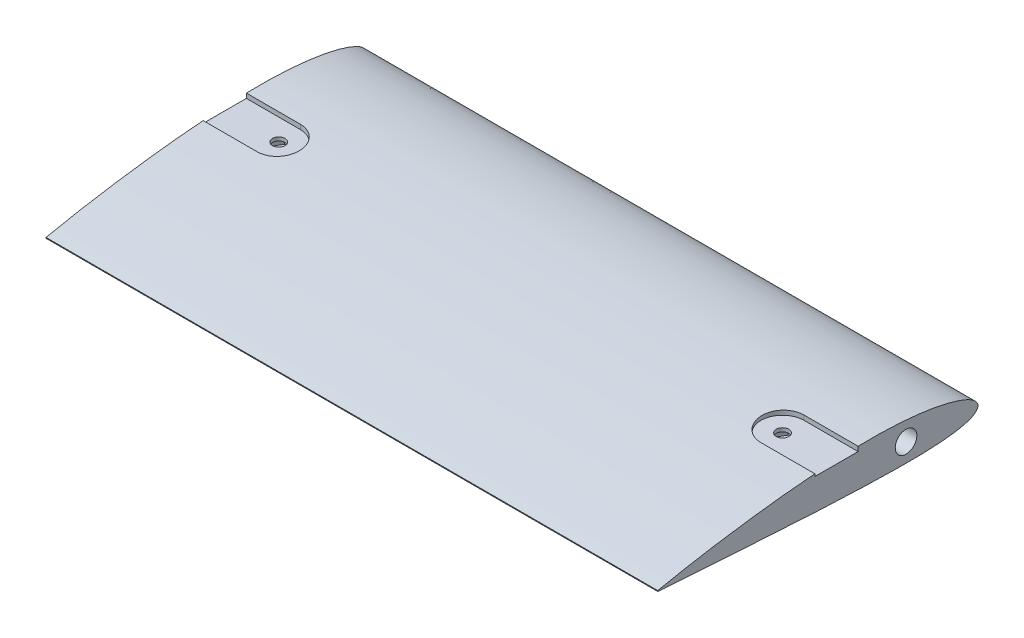
SolidWorks part; units mm, degrees
ref_plane "Front Plane" through (0, 0, 0) normal (0, 0, 1) x (1, 0, 0)
ref_plane "Top Plane" through (0, 0, 0) normal (0, 1, 0) x (1, 0, 0)
ref_plane "Right Plane" through (0, 0, 0) normal (1, 0, 0) x (0, 0, -1)
sketch "Sketch4" plane through (0, 0, 0) normal (0, 0, 1) x (1, 0, 0)
  line L0 (-30.3109, 17.5) -> (30.3109, 17.5)
  arc A1 (30.3109, 17.5) -> (-30.3109, 17.5) centre (0, 0) ccw
  dimension "D1" = 35
  dimension "D2" = 17.5
extrude "Exterior" add sketch "Sketch4" along normal blind 89 contours L0 A1
sketch "Sketch5" plane through (0, 0, 0) normal (0, 0, -1) x (-1, 0, 0)
  line L0 (30.3109, 17.5) -> (-30.3109, 17.5) construction
  line L1 (23.1247, 17.5) -> (-23.1247, 17.5)
  arc A0 (23.1247, 17.5) -> (-23.1247, 17.5) centre (0, 0) ccw
  dimension "D1" = 58
extrude "Boss-Extrude1" add sketch "Sketch5" along normal blind 15
curve "Curve3"
  spline degree 3 poles (0, 1.3, 1000) (0, 4.7133, 983.3426) (0, 11.531, 950.0715) (0, 24.0186, 883.4722) (0, 37.8548, 800.1781) (0, 52.175, 700.1592) (0, 64.1175, 600.1567) (0, 72.8619, 500.1109) (0, 78.7837, 400.0878) (0, 79.786, 316.6355) (0, 77.0249, 249.9395) (0, 72.979, 199.8766) (0, 66.5721, 149.7505) (0, 58.6825, 108.0331) (0, 49.7566, 74.7751) (0, 41.6416, 49.5609) (0, 32.1864, 28.1982) (0, 20.723, 9.771) (0, 0.8988, -6.2982) (0, -16.5264, 10.3934) (0, -24.4739, 28.476) (0, -30.5108, 49.7447) (0, -34.8393, 74.8759) (0, -38.5332, 108.2669) (0, -41.3764, 149.947) (0, -42.5163, 199.9941) (0, -42.3574, 250.0055) (0, -40.8857, 316.6783) (0, -38.2375, 400.0272) (0, -33.6287, 500.0334) (0, -27.6385, 600.0106) (0, -21.4122, 700.0048) (0, -15.1098, 800.0161) (0, -9.3053, 883.3314) (0, -4.8282, 950.0042) (0, -2.4761, 983.334) (0, -1.3, 1000) knots 0 0 0 0 0.025012 0.049959 0.099673 0.149206 0.198581 0.247805 0.296917 0.345953 0.370492 0.395091 0.419815 0.444799 0.45749 0.470406 0.483879 0.491264 0.503459 0.513609 0.520451 0.533235 0.545691 0.558032 0.582609 0.607135 0.631652 0.656174 0.705234 0.75432 0.803437 0.852566 0.901701 0.950849 0.975423 1 1 1 1
sketch "Sketch7" plane through (0, 0, 0) normal (1, 0, 0) x (0, 0, -1)
  line L0 (-89, 21.3887) -> (-89, 21.1573)
  line L1 (-89, 21.273) -> (0, 21.3903) construction
  line L2 (0, 21.3903) -> (-0.0573, 64.8516) construction
  line L7 (-89, 17.5) -> (0, 17.5) construction
  line L9 (0, 17.5) -> (0, 29) construction
  spline S1 degree 3 poles (-89, 21.3887) (-87.5176, 21.6924) (-84.5567, 22.2992) (-78.6297, 23.4105) (-71.2171, 24.6418) (-62.316, 25.9162) (-53.4164, 26.979) (-44.5129, 27.7573) (-35.6114, 28.2842) (-28.1847, 28.3735) (-22.2492, 28.1277) (-17.7939, 27.7677) (-13.3329, 27.1975) (-9.6203, 26.4954) (-6.6606, 25.701) (-4.4167, 24.9788) (-2.5155, 24.1374) (-0.8756, 23.1172) (0.5545, 21.353) (-0.931, 19.8022) (-2.5402, 19.095) (-4.433, 18.5577) (-6.6696, 18.1725) (-9.6412, 17.8438) (-13.3504, 17.5907) (-17.8043, 17.4893) (-22.255, 17.5034) (-28.1885, 17.6344) (-35.606, 17.8701) (-44.506, 18.2802) (-53.4034, 18.8133) (-62.3022, 19.3674) (-71.2026, 19.9283) (-78.6172, 20.4449) (-84.5507, 20.8433) (-87.5168, 21.0526) (-89, 21.1573) knots 0 0 0 0 0.025012 0.049959 0.099673 0.149206 0.198581 0.247805 0.296917 0.345953 0.370492 0.395091 0.419815 0.444799 0.45749 0.470406 0.483879 0.491264 0.503459 0.513609 0.520451 0.533235 0.545691 0.558032 0.582609 0.607135 0.631652 0.656174 0.705234 0.75432 0.803437 0.852566 0.901701 0.950849 0.975423 1 1 1 1
  dimension "D1" = 89
ref_plane "Plane1" through (80, 0, 0) normal (1, 0, 0) x (0, 0, -1)
ref_plane "Plane2" through (-80, 0, 0) normal (1, 0, 0) x (0, 0, -1)
sketch "Sketch8" plane through (80, 0, 0) normal (1, 0, 0) x (0, 0, -1)
  line L0 (-89, 21.3887) -> (-89, 21.1573)
  spline S0 degree 3 poles (-469.3669, 946.2185) (-209.3584, -26.81) (-147.9272, 10.417) (-78.6297, 23.4105) (-71.2171, 24.6418) (-62.316, 25.9162) (-53.4164, 26.979) (-44.5129, 27.7573) (-35.6114, 28.2842) (-28.1847, 28.3735) (-22.2492, 28.1277) (-17.7939, 27.7677) (-13.3329, 27.1975) (-9.6203, 26.4954) (-6.6606, 25.701) (-4.4167, 24.9788) (-2.5155, 24.1374) (-0.8756, 23.1172) (0.5545, 21.353) (-0.931, 19.8022) (-2.5402, 19.095) (-4.433, 18.5577) (-6.6696, 18.1725) (-9.6412, 17.8438) (-13.3504, 17.5907) (-17.8043, 17.4893) (-22.255, 17.5034) (-28.1885, 17.6344) (-35.606, 17.8701) (-44.506, 18.2802) (-53.4034, 18.8133) (-62.3022, 19.3674) (-71.2026, 19.9283) (-78.6172, 20.4449) (-191.4759, 28.0234) (-300.415, 49.2551) (-474.7288, -901.4445) knots -1.065698 -1.065698 -1.065698 -1.065698 0.025012 0.049959 0.099673 0.149206 0.198581 0.247805 0.296917 0.345953 0.370492 0.395091 0.419815 0.444799 0.45749 0.470406 0.483879 0.491264 0.503459 0.513609 0.520451 0.533235 0.545691 0.558032 0.582609 0.607135 0.631652 0.656174 0.705234 0.75432 0.803437 0.852566 0.901701 0.950849 0.975423 2.771414 2.771414 2.771414 2.771414 only from (-89, 21.3887) to (-89, 21.1573) construction
  spline S1 degree 3 poles (-89, 21.3887) (-87.5176, 21.6924) (-84.5567, 22.2992) (-78.6297, 23.4105) (-71.2171, 24.6418) (-62.316, 25.9162) (-53.4164, 26.979) (-44.5129, 27.7573) (-35.6114, 28.2842) (-28.1847, 28.3735) (-22.2492, 28.1277) (-17.7939, 27.7677) (-13.3329, 27.1975) (-9.6203, 26.4954) (-6.6606, 25.701) (-4.4167, 24.9788) (-2.5155, 24.1374) (-0.8756, 23.1172) (0.5545, 21.353) (-0.931, 19.8022) (-2.5402, 19.095) (-4.433, 18.5577) (-6.6696, 18.1725) (-9.6412, 17.8438) (-13.3504, 17.5907) (-17.8043, 17.4893) (-22.255, 17.5034) (-28.1885, 17.6344) (-35.606, 17.8701) (-44.506, 18.2802) (-53.4034, 18.8133) (-62.3022, 19.3674) (-71.2026, 19.9283) (-78.6172, 20.4449) (-84.5507, 20.8433) (-87.5168, 21.0526) (-89, 21.1573) knots 0 0 0 0 0.025012 0.049959 0.099673 0.149206 0.198581 0.247805 0.296917 0.345953 0.370492 0.395091 0.419815 0.444799 0.45749 0.470406 0.483879 0.491264 0.503459 0.513609 0.520451 0.533235 0.545691 0.558032 0.582609 0.607135 0.631652 0.656174 0.705234 0.75432 0.803437 0.852566 0.901701 0.950849 0.975423 1 1 1 1
sketch "Sketch9" plane through (-80, 0, 0) normal (1, 0, 0) x (0, 0, -1)
  line L0 (-89, 21.3887) -> (-89, 21.1573)
  spline S0 degree 3 poles (-469.3669, 946.2185) (-209.3584, -26.81) (-147.9272, 10.417) (-78.6297, 23.4105) (-71.2171, 24.6418) (-62.316, 25.9162) (-53.4164, 26.979) (-44.5129, 27.7573) (-35.6114, 28.2842) (-28.1847, 28.3735) (-22.2492, 28.1277) (-17.7939, 27.7677) (-13.3329, 27.1975) (-9.6203, 26.4954) (-6.6606, 25.701) (-4.4167, 24.9788) (-2.5155, 24.1374) (-0.8756, 23.1172) (0.5545, 21.353) (-0.931, 19.8022) (-2.5402, 19.095) (-4.433, 18.5577) (-6.6696, 18.1725) (-9.6412, 17.8438) (-13.3504, 17.5907) (-17.8043, 17.4893) (-22.255, 17.5034) (-28.1885, 17.6344) (-35.606, 17.8701) (-44.506, 18.2802) (-53.4034, 18.8133) (-62.3022, 19.3674) (-71.2026, 19.9283) (-78.6172, 20.4449) (-191.4759, 28.0234) (-300.415, 49.2551) (-474.7288, -901.4445) knots -1.065698 -1.065698 -1.065698 -1.065698 0.025012 0.049959 0.099673 0.149206 0.198581 0.247805 0.296917 0.345953 0.370492 0.395091 0.419815 0.444799 0.45749 0.470406 0.483879 0.491264 0.503459 0.513609 0.520451 0.533235 0.545691 0.558032 0.582609 0.607135 0.631652 0.656174 0.705234 0.75432 0.803437 0.852566 0.901701 0.950849 0.975423 2.771414 2.771414 2.771414 2.771414 only from (-89, 21.3887) to (-89, 21.1573) construction
  spline S1 degree 3 poles (-89, 21.3887) (-87.5176, 21.6924) (-84.5567, 22.2992) (-78.6297, 23.4105) (-71.2171, 24.6418) (-62.316, 25.9162) (-53.4164, 26.979) (-44.5129, 27.7573) (-35.6114, 28.2842) (-28.1847, 28.3735) (-22.2492, 28.1277) (-17.7939, 27.7677) (-13.3329, 27.1975) (-9.6203, 26.4954) (-6.6606, 25.701) (-4.4167, 24.9788) (-2.5155, 24.1374) (-0.8756, 23.1172) (0.5545, 21.353) (-0.931, 19.8022) (-2.5402, 19.095) (-4.433, 18.5577) (-6.6696, 18.1725) (-9.6412, 17.8438) (-13.3504, 17.5907) (-17.8043, 17.4893) (-22.255, 17.5034) (-28.1885, 17.6344) (-35.606, 17.8701) (-44.506, 18.2802) (-53.4034, 18.8133) (-62.3022, 19.3674) (-71.2026, 19.9283) (-78.6172, 20.4449) (-84.5507, 20.8433) (-87.5168, 21.0526) (-89, 21.1573) knots 0 0 0 0 0.025012 0.049959 0.099673 0.149206 0.198581 0.247805 0.296917 0.345953 0.370492 0.395091 0.419815 0.444799 0.45749 0.470406 0.483879 0.491264 0.503459 0.513609 0.520451 0.533235 0.545691 0.558032 0.582609 0.607135 0.631652 0.656174 0.705234 0.75432 0.803437 0.852566 0.901701 0.950849 0.975423 1 1 1 1
loft "Loft9" add profiles "Sketch8", "Sketch9"
sketch "Sketch12" plane through (80, 0, 0) normal (1, 0, 0) x (0, 0, -1)
  line L0 (-89, 21.3887) -> (-89, 21.1573) construction
  line L1 (-89, 21.3887) -> (-89, 21.1573)
  line L2 (-89, 21.3887) -> (-97.2409, 26.9065)
  line L3 (-97.2409, 26.9065) -> (-90.2923, 42.7722)
  line L4 (-90.2923, 42.7722) -> (-30.1138, 44.0233)
  line L5 (-30.1138, 44.0233) -> (6.4186, 38.5184)
  line L6 (6.4186, 38.5184) -> (-0.0099, 28.9175)
  line L7 (0, 21.3903) -> (-0.0573, 64.8516) construction
  line L8 (-0.0099, 28.9175) -> (-30.6202, 28.3197)
  spline S0 degree 3 poles (-713.3875, 1915.884) (-239.966, -47.1163) (-164.6221, 7.2867) (-78.6297, 23.4105) (-71.2171, 24.6418) (-62.316, 25.9162) (-53.4164, 26.979) (-44.5129, 27.7573) (-35.6114, 28.2842) (-28.1847, 28.3735) (-22.2492, 28.1277) (-17.7939, 27.7677) (-13.3329, 27.1975) (-9.6203, 26.4954) (-6.6606, 25.701) (-4.4167, 24.9788) (-2.5155, 24.1374) (-0.8756, 23.1172) (0.5545, 21.353) (-0.931, 19.8022) (-2.5402, 19.095) (-4.433, 18.5577) (-6.6696, 18.1725) (-9.6412, 17.8438) (-13.3504, 17.5907) (-17.8043, 17.4893) (-22.255, 17.5034) (-28.1885, 17.6344) (-35.606, 17.8701) (-44.506, 18.2802) (-53.4034, 18.8133) (-62.3022, 19.3674) (-71.2026, 19.9283) (-78.6172, 20.4449) (-220.4152, 29.9667) (-357.7257, 61.3982) (-629.9057, -1889.2617) knots -1.346455 -1.346455 -1.346455 -1.346455 0.025012 0.049959 0.099673 0.149206 0.198581 0.247805 0.296917 0.345953 0.370492 0.395091 0.419815 0.444799 0.45749 0.470406 0.483879 0.491264 0.503459 0.513609 0.520451 0.533235 0.545691 0.558032 0.582609 0.607135 0.631652 0.656174 0.705234 0.75432 0.803437 0.852566 0.901701 0.950849 0.975423 3.250848 3.250848 3.250848 3.250848 only from (-89, 21.3887) to (-89, 21.1573) construction
  spline S1 degree 3 poles (-89, 21.3887) (-87.5176, 21.6924) (-84.5567, 22.2992) (-78.6297, 23.4105) (-71.2171, 24.6418) (-62.316, 25.9162) (-53.4164, 26.979) (-44.5129, 27.7573) (-36.9147, 28.2071) (-32.2817, 28.3107) (-30.6202, 28.3197) knots 0 0 0 0 0.025012 0.049959 0.099673 0.149206 0.198581 0.247805 0.296917 0.324377 0.324377 0.324377 0.324377
  spline S2 degree 3 poles (-89, 21.3887) (-87.5176, 21.6924) (-84.5567, 22.2992) (-78.6297, 23.4105) (-71.2171, 24.6418) (-62.316, 25.9162) (-53.4164, 26.979) (-44.5129, 27.7573) (-36.9147, 28.2071) (-32.2817, 28.3107) (-30.6202, 28.3197) knots 0 0 0 0 0.025012 0.049959 0.099673 0.149206 0.198581 0.247805 0.296917 0.324377 0.324377 0.324377 0.324377
extrude "Cut-Extrude1" cut sketch "Sketch12" against normal through all
ref_plane "Plane3" through (0, 30, 0) normal (0, 1, 0) x (1, 0, 0)
sketch "Sketch17" plane through (-80, 0, 0) normal (-1, 0, 0) x (0, 0, 1)
  line L0 (89, 21.3887) -> (89, 21.1573) construction
  line L1 (89, 21.3887) -> (89, 21.1573)
  spline S0 degree 3 poles (713.3875, 1915.884) (239.966, -47.1163) (164.6221, 7.2867) (78.6297, 23.4105) (71.2171, 24.6418) (62.316, 25.9162) (53.4164, 26.979) (44.5129, 27.7573) (35.6114, 28.2842) (28.1847, 28.3735) (22.2492, 28.1277) (17.7939, 27.7677) (13.3329, 27.1975) (9.6203, 26.4954) (6.6606, 25.701) (4.4167, 24.9788) (2.5155, 24.1374) (0.8756, 23.1172) (-0.5545, 21.353) (0.931, 19.8022) (2.5402, 19.095) (4.433, 18.5577) (6.6696, 18.1725) (9.6412, 17.8438) (13.3504, 17.5907) (17.8043, 17.4893) (22.255, 17.5034) (28.1885, 17.6344) (35.606, 17.8701) (44.506, 18.2802) (53.4034, 18.8133) (62.3022, 19.3674) (71.2026, 19.9283) (78.6172, 20.4449) (220.4152, 29.9667) (357.7257, 61.3982) (629.9057, -1889.2617) knots -1.346455 -1.346455 -1.346455 -1.346455 0.025012 0.049959 0.099673 0.149206 0.198581 0.247805 0.296917 0.345953 0.370492 0.395091 0.419815 0.444799 0.45749 0.470406 0.483879 0.491264 0.503459 0.513609 0.520451 0.533235 0.545691 0.558032 0.582609 0.607135 0.631652 0.656174 0.705234 0.75432 0.803437 0.852566 0.901701 0.950849 0.975423 3.250848 3.250848 3.250848 3.250848 only from (89, 21.3887) to (89, 21.1573) construction
  spline S1 degree 3 poles (89, 21.3887) (87.5176, 21.6924) (84.5567, 22.2992) (78.6297, 23.4105) (71.2171, 24.6418) (62.316, 25.9162) (53.4164, 26.979) (44.5129, 27.7573) (35.6114, 28.2842) (28.1847, 28.3735) (22.2492, 28.1277) (17.7939, 27.7677) (13.3329, 27.1975) (9.6203, 26.4954) (6.6606, 25.701) (4.4167, 24.9788) (2.5155, 24.1374) (0.8756, 23.1172) (-0.5545, 21.353) (0.931, 19.8022) (2.5402, 19.095) (4.433, 18.5577) (6.6696, 18.1725) (9.6412, 17.8438) (13.3504, 17.5907) (17.8043, 17.4893) (22.255, 17.5034) (28.1885, 17.6344) (35.606, 17.8701) (44.506, 18.2802) (53.4034, 18.8133) (62.3022, 19.3674) (71.2026, 19.9283) (78.6172, 20.4449) (84.5507, 20.8433) (87.5168, 21.0526) (89, 21.1573) knots 0 0 0 0 0.025012 0.049959 0.099673 0.149206 0.198581 0.247805 0.296917 0.345953 0.370492 0.395091 0.419815 0.444799 0.45749 0.470406 0.483879 0.491264 0.503459 0.513609 0.520451 0.533235 0.545691 0.558032 0.582609 0.607135 0.631652 0.656174 0.705234 0.75432 0.803437 0.852566 0.901701 0.950849 0.975423 1 1 1 1
extrude "Boss-Extrude2" add sketch "Sketch17" along normal blind 170
sketch "Sketch14" plane through (0, 30, 0) normal (0, 1, 0) x (1, 0, 0)
  line L0 (-95, -33.3225) -> (-65, -33.3225)
  line L1 (-95, -45.3225) -> (-65, -45.3225)
  line L2 (-80, -89) -> (-80, 0) construction
  line L3 (-80, -89) -> (-80, 0) construction
  line L4 (-95, -39.3225) -> (-65, -39.3225) construction
  arc A0 (-65, -45.3225) -> (-65, -33.3225) centre (-65, -39.3225) ccw
  arc A1 (-95, -33.3225) -> (-95, -45.3225) centre (-95, -39.3225) ccw
  point P8 (-80, -39.3225)
  dimension "D2" = 6
  dimension "D1" = 30
extrude "Cut-Extrude3" cut sketch "Sketch14" against normal blind 3
sketch "Sketch15" plane through (0, 27, 0) normal (0, 1, 0) x (1, 0, 0)
  line L0 (-80, -89) -> (-80, 0) construction
  line L1 (-80, -89) -> (-80, 0) construction
  circle A0 centre (-65, -39.3225) radius 1.75
  circle A1 centre (-95, -39.3225) radius 1.75
  dimension "D1" = 3.5
extrude "Cut-Extrude4" cut sketch "Sketch15" against normal blind 4
ref_plane "Plane4" through (0, 23.5, 0) normal (0, 1, 0) x (1, 0, 0)
sketch "Sketch16" plane through (0, 23.5, 0) normal (0, 1, 0) x (1, 0, 0)
  line L0 (-80, -89) -> (-80, 0) construction
  line L1 (-67.1651, -43.0725) -> (-62.8349, -43.0725)
  line L2 (-62.8349, -43.0725) -> (-60.6699, -39.3225)
  line L3 (-60.6699, -39.3225) -> (-62.8349, -35.5725)
  line L4 (-62.8349, -35.5725) -> (-67.1651, -35.5725)
  line L5 (-67.1651, -35.5725) -> (-69.3301, -39.3225)
  line L6 (-69.3301, -39.3225) -> (-67.1651, -43.0725)
  line L7 (-80, -89) -> (-80, 0) construction
  line L8 (-90.6699, -39.3225) -> (-92.8349, -43.0725)
  line L9 (-92.8349, -43.0725) -> (-97.1651, -43.0725)
  line L10 (-97.1651, -43.0725) -> (-99.3301, -39.3225)
  line L11 (-99.3301, -39.3225) -> (-97.1651, -35.5725)
  line L12 (-97.1651, -35.5725) -> (-92.8349, -35.5725)
  line L13 (-92.8349, -35.5725) -> (-90.6699, -39.3225)
  circle A0 centre (-65, -39.3225) radius 3.75 construction
  dimension "D1" = 7.5
extrude "Cut-Extrude5" cut sketch "Sketch16" along normal blind 2.5
mirror "Mirror1" about plane through (0, 0, 0) normal (1, 0, 0) of "Cut-Extrude5", "Cut-Extrude4", "Cut-Extrude3"
ref_plane "Plane5" through (-165, 0, 0) normal (1, 0, 0) x (0, 0, -1)
mirror "Mirror2" about plane through (-165, 0, 0) normal (1, 0, 0) of "Cut-Extrude5", "Cut-Extrude3", "Cut-Extrude4"
ref_plane "Plane6" through (-80, 0, 0) normal (1, 0, 0) x (0, 0, -1)
sketch "Sketch18" plane through (-80, 0, 0) normal (1, 0, 0) x (0, 0, -1)
  line L0 (-99.867, 5.7154) -> (-104.3901, 63.3258)
  line L1 (-104.3901, 63.3258) -> (31.8989, 60.8261)
  line L2 (31.8989, 60.8261) -> (39.2788, -3.2119)
  line L3 (39.2788, -3.2119) -> (-99.867, 5.7154)
extrude "Cut-Extrude6" cut sketch "Sketch18" along normal through all
sketch "Sketch13" plane through (-80, 0, 0) normal (-1, 0, 0) x (0, 0, 1)
  line L0 (20, 17.5005) -> (20, 27.9379) construction
  circle A0 centre (20, 22.7192) radius 3
  spline S0 degree 3 poles (89, 21.3887) (87.5176, 21.6924) (84.5567, 22.2992) (78.6297, 23.4105) (71.2171, 24.6418) (62.316, 25.9162) (53.4164, 26.979) (44.5129, 27.7573) (35.6114, 28.2842) (28.1847, 28.3735) (22.2492, 28.1277) (17.7939, 27.7677) (13.3329, 27.1975) (9.6203, 26.4954) (6.6606, 25.701) (4.4167, 24.9788) (2.5155, 24.1374) (0.8756, 23.1172) (-0.5545, 21.353) (0.931, 19.8022) (2.5402, 19.095) (4.433, 18.5577) (6.6696, 18.1725) (9.6412, 17.8438) (13.3504, 17.5907) (17.8043, 17.4893) (22.255, 17.5034) (28.1885, 17.6344) (35.606, 17.8701) (44.506, 18.2802) (53.4034, 18.8133) (62.3022, 19.3674) (71.2026, 19.9283) (78.6172, 20.4449) (84.5507, 20.8433) (87.5168, 21.0526) (89, 21.1573) knots 0 0 0 0 0.025012 0.049959 0.099673 0.149206 0.198581 0.247805 0.296917 0.345953 0.370492 0.395091 0.419815 0.444799 0.45749 0.470406 0.483879 0.491264 0.503459 0.513609 0.520451 0.533235 0.545691 0.558032 0.582609 0.607135 0.631652 0.656174 0.705234 0.75432 0.803437 0.852566 0.901701 0.950849 0.975423 1 1 1 1 construction
  point P8 (20, 22.7192)
  dimension "D1" = 6
  dimension "D2" = 20
extrude "Cut-Extrude2" cut sketch "Sketch13" against normal through all and the other way through all
equation "\"fuse_diam\"= 0.07"
equation "\"fuse_rad\"= 0.035"
equation "\"battery_length\"= 0.076"
equation "\"battery_width\"= 0.034"
equation "\"battery_height\"= 0.051"
equation "\"bat_bay_length\"= 0.096"
equation "\"shell\"= 0.002"
equation "\"D1@Exterior\"=\"chord_length\""
equation "\"wing_shelf\"= 0.0175"
equation "\"chord_length\"= 0.089"
equation "\"tail_length\"= 0.26532000000000006"
equation "\"tail_diam\"= 0.035"
equation "\"connector\"= 0.06633000000000001"
equation "\"D2@Sketch4\"=\"wing_shelf\""
equation "\"D1@Sketch4\"=\"fuse_rad\""
equation "\"D1@Sketch5\"=\"fuse_diam\"-0.012"
equation "\"D1@Sketch7\"=\"chord_length\""
